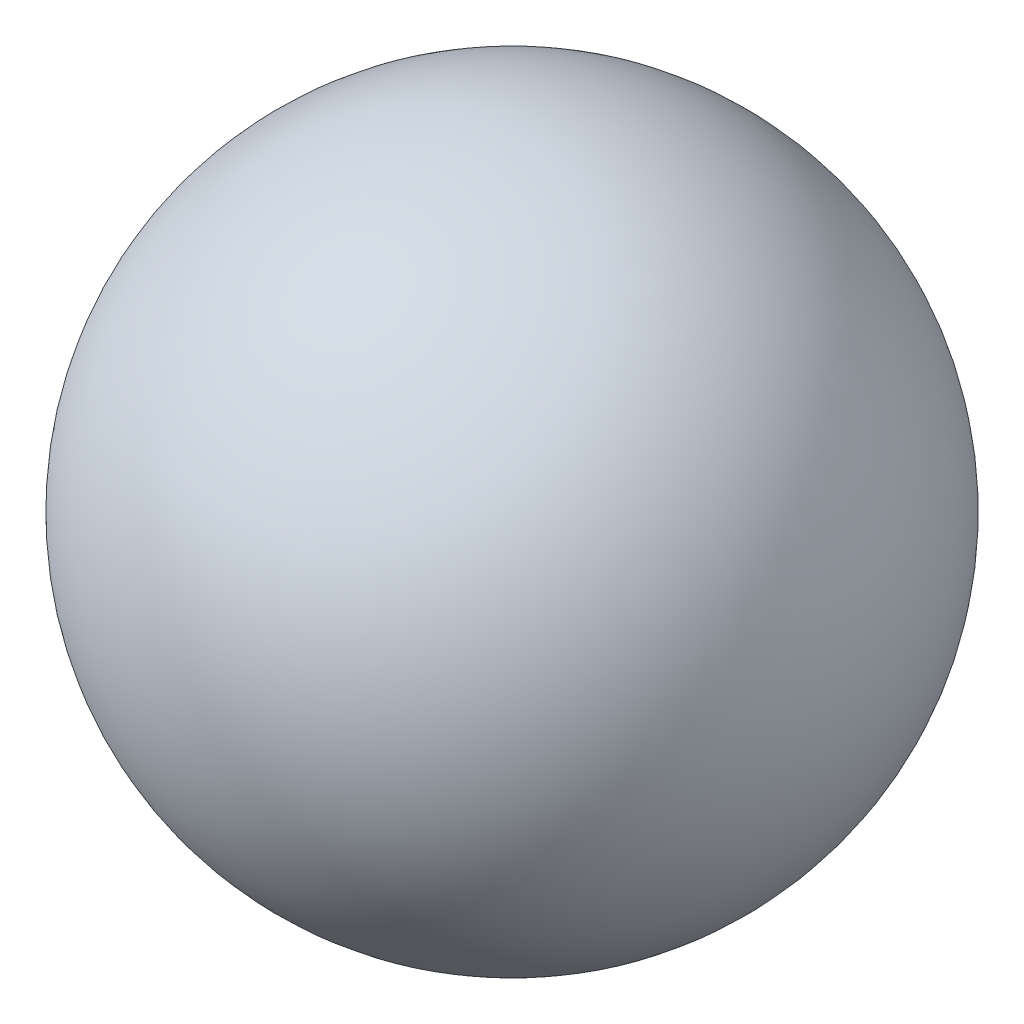
SolidWorks part; units mm, degrees
ref_plane "前视基准面" through (0, 0, 0) normal (0, 0, 1) x (1, 0, 0)
ref_plane "上视基准面" through (0, 0, 0) normal (0, 1, 0) x (1, 0, 0)
ref_plane "右视基准面" through (0, 0, 0) normal (1, 0, 0) x (0, 0, -1)
other "Configuration Table"
sketch "草图1" plane through (0, 0, 0) normal (0, 0, 1) x (1, 0, 0)
  line L0 (0, 9) -> (0, -9)
  arc A0 (0, -9) -> (0, 9) centre (0, 0) ccw
  dimension "D1" = 18
revolve "旋转1" add sketch "草图1" angle 360 about L0
